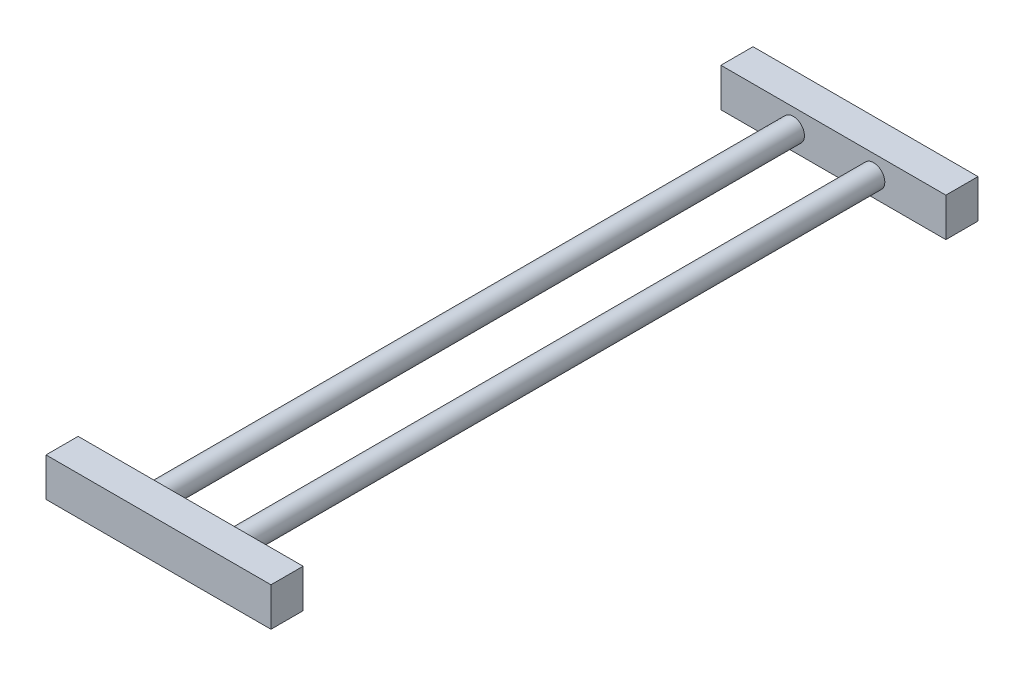
SolidWorks part; units mm, degrees
ref_plane "Plan de face" through (0, 0, 0) normal (0, 0, 1) x (1, 0, 0)
ref_plane "Plan de dessus" through (0, 0, 0) normal (0, 1, 0) x (1, 0, 0)
ref_plane "Plan de droite" through (0, 0, 0) normal (1, 0, 0) x (0, 0, -1)
sketch "Esquisse1" plane through (0, 0, 0) normal (0, 0, 1) x (1, 0, 0)
  line L0 (-15.4706, 10.7369) -> (9.5294, 10.7369) construction
  circle A0 centre (-15.4706, 10.7369) radius 3.5
  circle A1 centre (9.5294, 10.7369) radius 3.5
  dimension "D1" = 7
  dimension "D2" = 7
  dimension "D3" = 25
extrude "Boss.-Extru.1" add sketch "Esquisse1" along normal blind 200
sketch "Esquisse2" plane through (0, 0, 0) normal (0, 0, -1) x (-1, 0, 0)
  line L1 (37.9706, 4.7369) -> (-32.0294, 4.7369)
  line L2 (37.9706, 4.7369) -> (37.9706, 16.7369)
  line L3 (37.9706, 16.7369) -> (-32.0294, 16.7369)
  line L4 (-32.0294, 4.7369) -> (-32.0294, 16.7369)
  circle A0 centre (15.4706, 10.7369) radius 3.5 construction
  dimension "D1" = 12
  dimension "D2" = 70
  dimension "D3" = 6
  dimension "D4" = 22.5
extrude "Boss.-Extru.2" add sketch "Esquisse2" along normal blind 10
sketch "Esquisse3" plane through (0, 0, 200) normal (0, 0, 1) x (1, 0, 0)
  line L4 (-37.9706, 16.7369) -> (-37.9706, 4.7369)
  line L5 (-37.9706, 4.7369) -> (32.0294, 4.7369)
  line L6 (32.0294, 4.7369) -> (32.0294, 16.7369)
  line L7 (32.0294, 16.7369) -> (-37.9706, 16.7369)
  line L8 (-37.9706, 16.7369) -> (-37.9706, 4.7369)
  line L9 (-37.9706, 4.7369) -> (32.0294, 4.7369)
  line L10 (32.0294, 4.7369) -> (32.0294, 16.7369)
  line L11 (32.0294, 16.7369) -> (-37.9706, 16.7369)
  dimension "D1" = 0
extrude "Boss.-Extru.3" add sketch "Esquisse3" along normal blind 10
